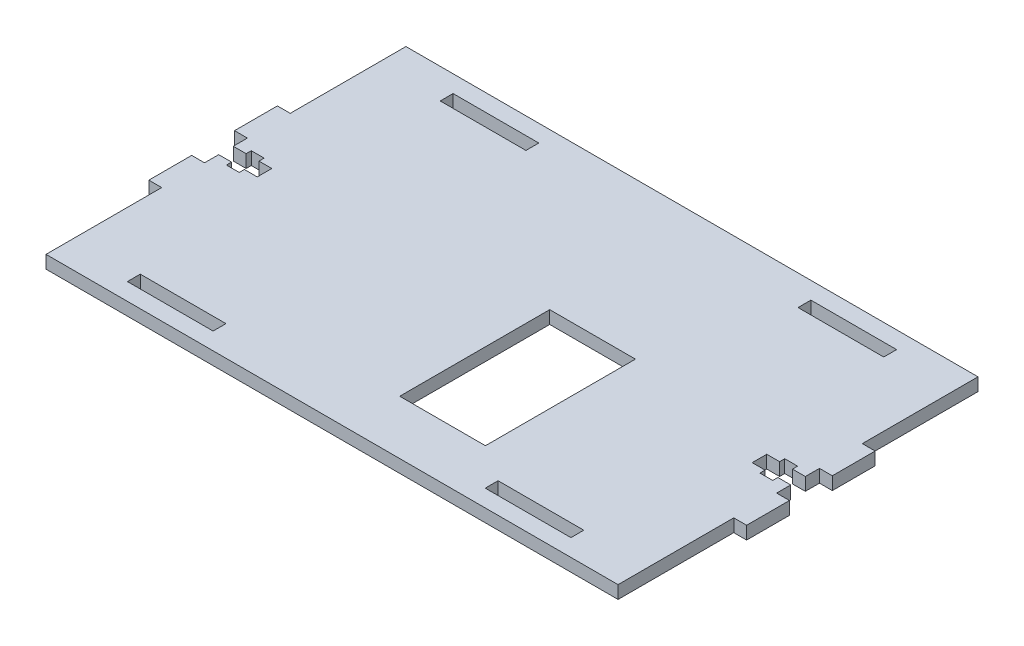
SolidWorks part; units mm, degrees
ref_plane "Спереди" through (0, 0, 0) normal (0, 0, 1) x (1, 0, 0)
ref_plane "Сверху" through (0, 0, 0) normal (0, 1, 0) x (1, 0, 0)
ref_plane "Справа" through (0, 0, 0) normal (1, 0, 0) x (0, 0, -1)
sketch "Sketch1" plane through (0, 0, 0) normal (0, 1, 0) x (1, 0, 0)
  line L0 (53.8429, -48.0568) -> (-9.6571, -48.0568) construction
  line L1 (-44.6571, 31.9432) -> (88.8429, 31.9432)
  line L2 (-44.6571, 31.9432) -> (-44.6571, -52.0568)
  line L3 (-44.6571, -52.0568) -> (88.8429, -52.0568)
  line L4 (88.8429, 31.9432) -> (88.8429, -52.0568)
  line L5 (88.8429, 27.9432) -> (88.8429, 24.9432) construction
  dimension "D1" = 4
extrude "Boss-Extrude1" add sketch "Sketch1" along normal blind 3
sketch "Sketch2" plane through (0, 0, 0) normal (0, -1, 0) x (1, 0, 0)
  line L0 (53.8429, 45.0568) -> (73.8429, 45.0568) construction
  line L1 (73.8429, 45.0568) -> (73.8429, 48.0568) construction
  line L2 (73.8429, 48.0568) -> (53.8429, 48.0568) construction
  line L3 (53.8429, 48.0568) -> (53.8429, 45.0568) construction
  line L4 (-29.6571, 45.0568) -> (-9.6571, 45.0568) construction
  line L5 (-9.6571, 45.0568) -> (-9.6571, 48.0568) construction
  line L6 (-9.6571, 48.0568) -> (-29.6571, 48.0568) construction
  line L7 (-29.6571, 48.0568) -> (-29.6571, 45.0568) construction
  line L8 (-29.6571, -27.9432) -> (-9.6571, -27.9432) construction
  line L9 (-9.6571, -27.9432) -> (-9.6571, -24.9432) construction
  line L10 (-9.6571, -24.9432) -> (-29.6571, -24.9432) construction
  line L11 (-29.6571, -24.9432) -> (-29.6571, -27.9432) construction
  line L12 (53.8429, -27.9432) -> (73.8429, -27.9432) construction
  line L13 (73.8429, -27.9432) -> (73.8429, -24.9432) construction
  line L14 (73.8429, -24.9432) -> (53.8429, -24.9432) construction
  line L15 (53.8429, -24.9432) -> (53.8429, -27.9432) construction
  line L16 (53.8429, 45.0568) -> (73.8429, 45.0568)
  line L17 (73.8429, 45.0568) -> (73.8429, 48.0568)
  line L18 (73.8429, 48.0568) -> (53.8429, 48.0568)
  line L19 (53.8429, 48.0568) -> (53.8429, 45.0568)
  line L20 (-29.6571, 45.0568) -> (-9.6571, 45.0568)
  line L21 (-9.6571, 45.0568) -> (-9.6571, 48.0568)
  line L22 (-9.6571, 48.0568) -> (-29.6571, 48.0568)
  line L23 (-29.6571, 48.0568) -> (-29.6571, 45.0568)
  line L24 (-29.6571, -27.9432) -> (-9.6571, -27.9432)
  line L25 (-9.6571, -27.9432) -> (-9.6571, -24.9432)
  line L26 (-9.6571, -24.9432) -> (-29.6571, -24.9432)
  line L27 (-29.6571, -24.9432) -> (-29.6571, -27.9432)
  line L28 (53.8429, -27.9432) -> (73.8429, -27.9432)
  line L29 (73.8429, -27.9432) -> (73.8429, -24.9432)
  line L30 (73.8429, -24.9432) -> (53.8429, -24.9432)
  line L31 (53.8429, -24.9432) -> (53.8429, -27.9432)
extrude "Cut-Extrude1" cut sketch "Sketch2" against normal through all
sketch "Sketch3" plane through (0, 0, 0) normal (0, -1, 0) x (1, 0, 0)
  line L0 (-44.6571, -31.9432) -> (-44.6571, 52.0568) construction
  line L1 (91.8429, -4.9432) -> (88.8429, -4.9432)
  line L2 (91.8429, -4.9432) -> (91.8429, 25.0568)
  line L3 (91.8429, 25.0568) -> (88.8429, 25.0568)
  line L4 (88.8429, -4.9432) -> (88.8429, 25.0568)
  line L5 (91.8429, -4.9432) -> (88.8429, 25.0568) construction
  line L6 (91.8429, 25.0568) -> (88.8429, -4.9432) construction
  line L7 (-44.6571, -4.9432) -> (-47.6571, -4.9432)
  line L8 (-44.6571, -4.9432) -> (-44.6571, 25.0568)
  line L9 (-44.6571, 25.0568) -> (-47.6571, 25.0568)
  line L10 (-47.6571, -4.9432) -> (-47.6571, 25.0568)
  line L11 (-44.6571, -4.9432) -> (-47.6571, 25.0568) construction
  line L12 (-44.6571, 25.0568) -> (-47.6571, -4.9432) construction
  line L13 (88.8429, 52.0568) -> (88.8429, -31.9432) construction
  point P0 (90.3429, 10.0568)
  point P5 (-46.1571, 10.0568)
  point P10 (0, 0)
  point P13 (-44.6571, 10.0568)
  dimension "D1" = 3
  dimension "D2" = 30
extrude "Boss-Extrude2" add sketch "Sketch3" against normal through all
sketch "Sketch4" plane through (0, 0, 0) normal (0, -1, 0) x (1, 0, 0)
  line L0 (88.8429, 5.0568) -> (94.8429, 5.0568)
  line L1 (88.8429, 5.0568) -> (88.8429, 15.0568)
  line L2 (88.8429, 15.0568) -> (94.8429, 15.0568)
  line L3 (94.8429, 5.0568) -> (94.8429, 15.0568)
  line L4 (88.8429, 5.0568) -> (94.8429, 15.0568) construction
  line L5 (88.8429, 15.0568) -> (94.8429, 5.0568) construction
  line L6 (88.8429, 8.3568) -> (85.8429, 8.3568)
  line L7 (88.8429, 8.3568) -> (88.8429, 11.7568)
  line L8 (88.8429, 11.7568) -> (85.8429, 11.7568)
  line L9 (85.8429, 8.3568) -> (85.8429, 11.7568)
  line L10 (88.8429, 8.3568) -> (85.8429, 11.7568) construction
  line L11 (88.8429, 11.7568) -> (85.8429, 8.3568) construction
  line L12 (85.8429, 7.1568) -> (82.8429, 7.1568)
  line L13 (85.8429, 7.1568) -> (85.8429, 12.9568)
  line L14 (85.8429, 12.9568) -> (82.8429, 12.9568)
  line L15 (82.8429, 7.1568) -> (82.8429, 12.9568)
  line L16 (85.8429, 7.1568) -> (82.8429, 12.9568) construction
  line L17 (85.8429, 12.9568) -> (82.8429, 7.1568) construction
  line L18 (88.8429, -4.9432) -> (88.8429, -31.9432) construction
  line L19 (91.8429, -4.9432) -> (91.8429, 25.0568) construction
  line L21 (79.8429, 11.7568) -> (82.8429, 11.7568)
  line L22 (79.8429, 11.7568) -> (79.8429, 8.3568)
  line L23 (79.8429, 8.3568) -> (82.8429, 8.3568)
  line L24 (82.8429, 11.7568) -> (82.8429, 8.3568)
  line L25 (79.8429, 11.7568) -> (82.8429, 8.3568) construction
  line L26 (79.8429, 8.3568) -> (82.8429, 11.7568) construction
  point P0 (91.8429, 10.0568)
  point P5 (87.3429, 10.0568)
  point P10 (84.3429, 10.0568)
  point P17 (81.3429, 10.0568)
  point P21 (91.8429, 10.0568)
  point P25 (0, 0)
  line M33 (91.8429, -4.9432) -> (91.8429, 25.0568)
  dimension "D1" = 10
  dimension "D2" = 3.4
  dimension "D3" = 3
  dimension "D4" = 3
  dimension "D5" = 5.8
extrude "Cut-Extrude2" cut sketch "Sketch4" against normal through all both and the other way through all contours L2 L1 L0 M33 | L9 L6 L1 L8 | L15 L12 L13 L9 L14 | L22 L23 L24 L21
sketch "Sketch5" plane through (0, 0, 0) normal (0, -1, 0) x (1, 0, 0)
  line L0 (-44.6571, 52.0568) -> (88.8429, -31.9432) construction
  line L1 (-44.6571, -31.9432) -> (88.8429, 52.0568) construction
  point P8 (22.0929, 10.0568)
ref_plane "Plane1" through (22.0929, 0, 0) normal (1, 0, 0) x (0, 0, -1)
mirror "Mirror1" about plane through (22.0929, 0, 0) normal (1, 0, 0) of "Cut-Extrude2"
sketch "Sketch6" plane through (0, 0, 0) normal (0, -1, 0) x (1, 0, 0)
  line L1 (45.2929, 4.4568) -> (25.2929, 4.4568)
  line L2 (45.2929, 4.4568) -> (45.2929, 39.4568)
  line L3 (45.2929, 39.4568) -> (25.2929, 39.4568)
  line L4 (25.2929, 4.4568) -> (25.2929, 39.4568)
  line L7 (43.2929, 6.4568) -> (27.2929, 6.4568) construction
  line L8 (40.8429, 37.4568) -> (28.6429, 37.4568) construction
  line L9 (27.2929, 6.4568) -> (27.2929, 19.9568) construction
  line L10 (43.2929, 6.4568) -> (43.2929, 19.9568) construction
  point P4 (26.5929, 39.0568)
  point P7 (42.4691, 39.0568)
  point P8 (0, 0)
  dimension "D1" = 2
  dimension "D2" = 2
  dimension "D3" = 2
  dimension "D4" = 2
extrude "Cut-Extrude3" cut sketch "Sketch6" against normal through all
